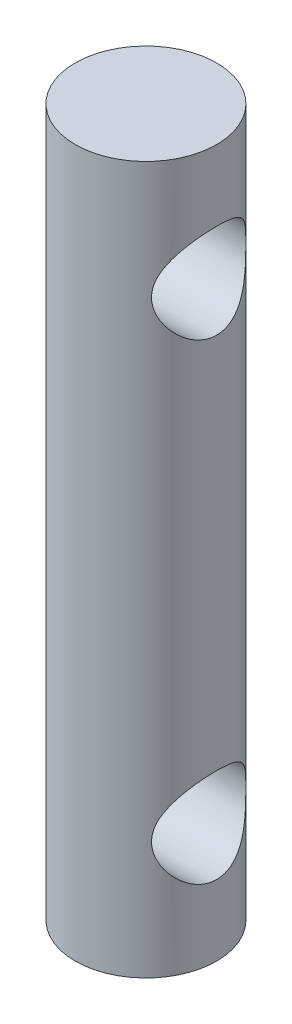
SolidWorks part; units mm, degrees
ref_plane "Płaszczyzna przednia" through (0, 0, 0) normal (0, 0, 1) x (1, 0, 0)
ref_plane "Płaszczyzna górna" through (0, 0, 0) normal (0, 1, 0) x (1, 0, 0)
ref_plane "Płaszczyzna prawa" through (0, 0, 0) normal (1, 0, 0) x (0, 0, -1)
sketch "Szkic1" plane through (0, 0, 0) normal (0, 1, 0) x (1, 0, 0)
  circle A0 centre (0, 0) radius 3
  dimension "D1" = 6
extrude "Dodanie-wyciągnięcie1" add sketch "Szkic1" along normal blind 30
sketch "Szkic2" plane through (0, 0, 0) normal (1, 0, 0) x (0, 0, -1)
  line L1 (3, 0) -> (3, 30) construction
  line L2 (-3, 15) -> (4.8988, 15) construction
  line L3 (-3, 30) -> (-3, 0) construction
  circle A0 centre (0, 25) radius 2
  circle A1 centre (0, 5) radius 2
  dimension "D1" = 4
  dimension "D2" = 20
  dimension "D3" = 3
extrude "Wytnij-wyciągnięcie1" cut sketch "Szkic2" against normal mid plane 15
